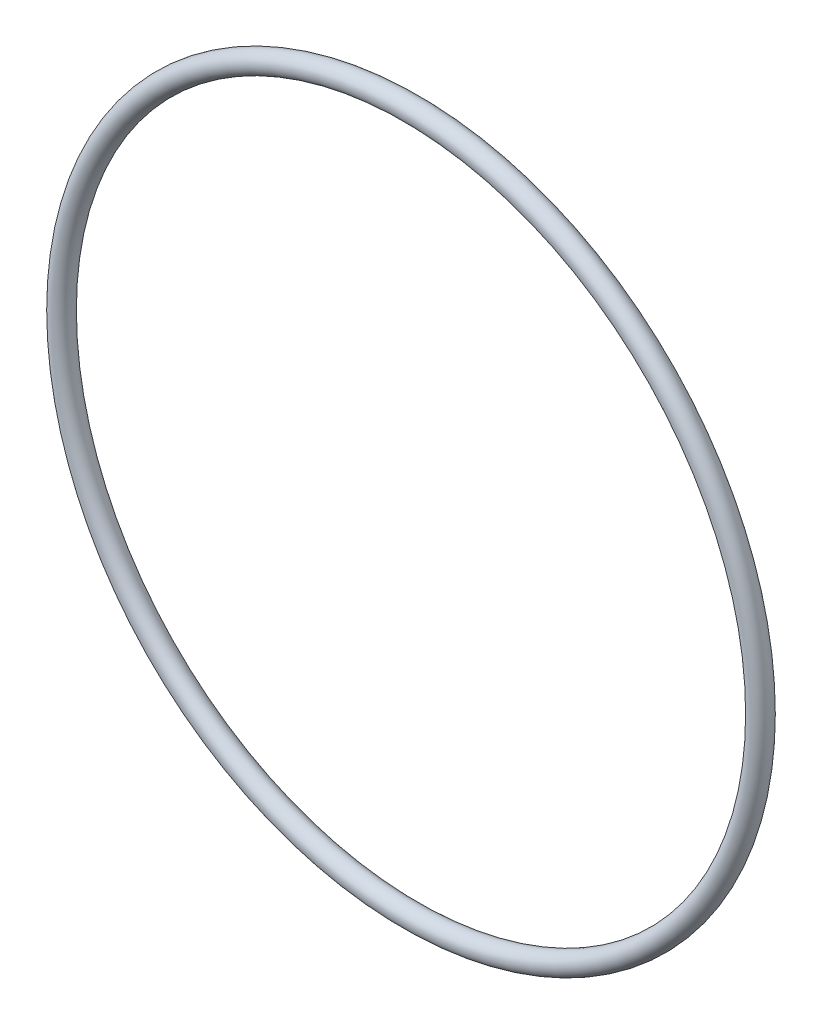
SolidWorks part; units mm, degrees
ref_plane "Front" through (0, 0, 0) normal (0, 0, 1) x (1, 0, 0)
ref_plane "Top" through (0, 0, 0) normal (0, 1, 0) x (1, 0, 0)
ref_plane "Right" through (0, 0, 0) normal (1, 0, 0) x (0, 0, -1)
sketch "Sketch1" plane through (0, 0, 0) normal (1, 0, 0) x (0, -1, 0)
  line L0 (0, -1.7653) -> (0, 1.7653) construction
  line L2 (-66.5251, 0) -> (66.5251, 0) construction
  line L3 (-56.9468, 0) -> (56.9468, 0) construction
  circle A0 centre (58.7121, 0) radius 1.7653
  point P9 (56.9468, 0)
  point P10 (60.4774, 0)
  point P13 (58.7121, 1.7653)
  point P14 (58.7121, -1.7653)
  dimension "Width" = 3.5306
  dimension "ID" = 113.8936
revolve "Revolve1" add sketch "Sketch1" angle 360 about L0
